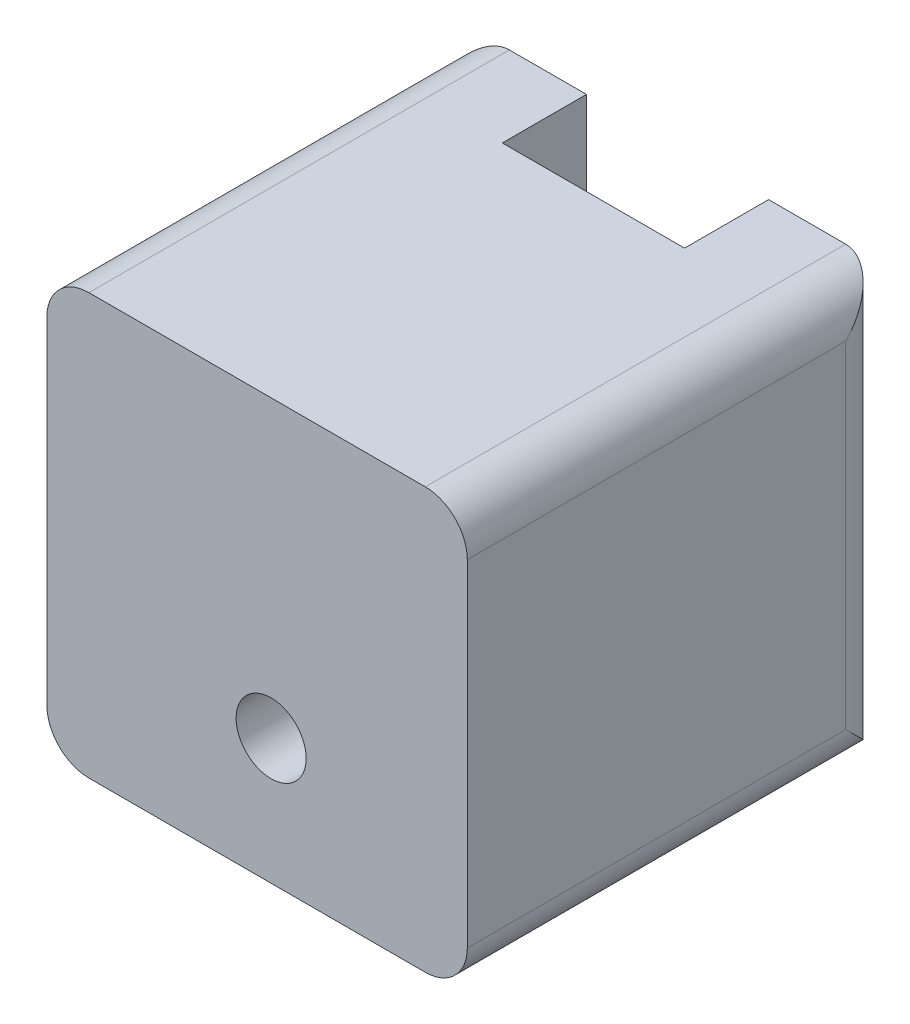
SolidWorks part; units mm, degrees
ref_plane "Front Plane" through (0, 0, 0) normal (0, 0, 1) x (1, 0, 0)
ref_plane "Top Plane" through (0, 0, 0) normal (0, 1, 0) x (1, 0, 0)
ref_plane "Right Plane" through (0, 0, 0) normal (1, 0, 0) x (0, 0, -1)
sketch "Esquisse1" plane through (0, 0, 0) normal (0, 0, 1) x (1, 0, 0)
  line L1 (0, 0) -> (-30, 0)
  line L2 (0, 0) -> (0, -30)
  line L3 (0, -30) -> (-30, -30)
  line L4 (-30, 0) -> (-30, -30)
  dimension "D1" = 30
  dimension "D2" = 30
extrude "Boss.-Extru.1" add sketch "Esquisse1" along normal blind 30
sketch "Esquisse2" plane through (0, 0, 0) normal (0, 0, -1) x (-1, 0, 0)
  line L0 (0, 0) -> (30, 0) construction
  line L1 (8.5, 0) -> (21.5, 0)
  line L2 (8.5, 0) -> (8.5, -15)
  line L3 (8.5, -15) -> (21.5, -15)
  line L4 (21.5, 0) -> (21.5, -15)
  line L5 (30, 0) -> (30, -30) construction
  line L6 (0, -30) -> (0, 0) construction
  dimension "D1" = 13
  dimension "D2" = 15
  dimension "D3" = 8.5
  dimension "D4" = 8.5
extrude "Enlèv. mat.-Extru.1" cut sketch "Esquisse2" against normal blind 6
sketch "Esquisse3" plane through (0, 0, 0) normal (0, 0, -1) x (-1, 0, 0)
  line L0 (30, -30) -> (0, -30) construction
  line L1 (21.5, -15) -> (18, -15)
  line L2 (21.5, -15) -> (21.5, -30)
  line L3 (21.5, -30) -> (18, -30)
  line L4 (18, -15) -> (18, -30)
  dimension "D1" = 3.5
extrude "Enlèv. mat.-Extru.2" cut sketch "Esquisse3" against normal blind 3
sketch "Esquisse4" plane through (0, 0, 0) normal (0, 0, -1) x (-1, 0, 0)
  line L0 (0, -30) -> (0, 0) construction
  circle A0 centre (14, -21.039) radius 2.5
  circle A1 centre (14, -21.039) radius 4
  dimension "D1" = 5
  dimension "D3" = 8
  dimension "D2" = 14
extrude "Enlèv. mat.-Extru.18" cut sketch "Esquisse4" against normal through all contours A0
fillet "Congé1" radius 3 6 edges at (0, 0, 15) (-30, 0, 15) (0, -30, 15) (-30, -30, 15) (0, -15, 0) (-30, -15, 0)
